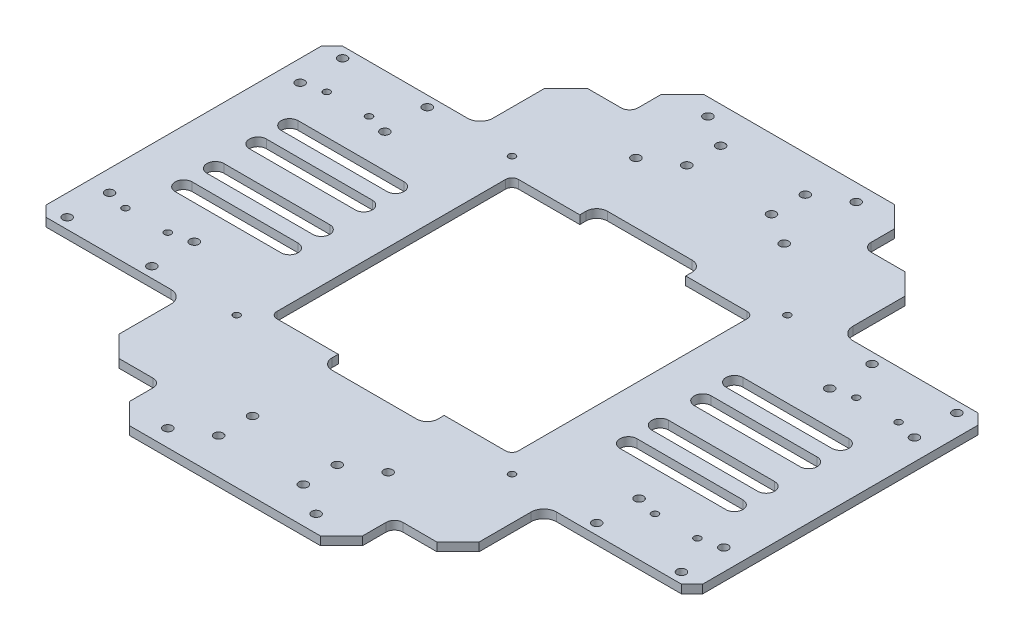
SolidWorks part; units mm, degrees
ref_plane "前视基准面" through (0, 0, 0) normal (0, 0, 1) x (1, 0, 0)
ref_plane "上视基准面" through (0, 0, 0) normal (0, 1, 0) x (1, 0, 0)
ref_plane "右视基准面" through (0, 0, 0) normal (1, 0, 0) x (0, 0, -1)
sketch "草图1" plane through (0, 0, 0) normal (0, 1, 0) x (1, 0, 0)
  line L0 (-55, 135.4999) -> (-55, -135.4999)
  line L1 (-55, -135.4999) -> (55, -135.4999)
  line L2 (55, -135.4999) -> (55, 135.4999)
  line L3 (55, 135.4999) -> (-55, 135.4999)
  circle A0 centre (-35, 127.4999) radius 2.1
  circle A1 centre (-20, 118.4999) radius 2.1
  circle A2 centre (20, 118.4999) radius 2.1
  circle A3 centre (35, 127.4999) radius 2.1
  circle A4 centre (20, 102.4999) radius 2.1
  circle A5 centre (35, 93.4999) radius 2.1
  circle A6 centre (-35, 93.4999) radius 2.1
  circle A7 centre (-20, 102.4999) radius 2.1
  circle A8 centre (-35, -127.4999) radius 2.1
  circle A9 centre (-20, -118.4999) radius 2.1
  circle A10 centre (-20, -102.4999) radius 2.1
  circle A11 centre (20, -118.4999) radius 2.1
  circle A12 centre (20, -102.4999) radius 2.1
  circle A13 centre (35, -93.4999) radius 2.1
  circle A14 centre (35, -127.4999) radius 2.1
extrude "凸台-拉伸1" add sketch "草图1" along normal blind 4
chamfer "倒角1" distance 10 angle 45 4 edges at (-55, 2, 135.4999) (55, 2, 135.4999) (55, 2, -135.4999) (-55, 2, -135.4999)
sketch "草图2" plane through (0, 4, 0) normal (0, 1, 0) x (1, 0, 0)
  line L0 (-25, 45) -> (-40, 30)
  line L1 (-25, -65) -> (25, -65)
  line L2 (-25, -65) -> (-25, -45)
  line L3 (-25, 65) -> (25, 65)
  line L4 (25, -65) -> (25, -45)
  line L5 (-25, -65) -> (25, 65) construction
  line L6 (-25, 65) -> (25, -65) construction
  line L7 (-40, 30) -> (-40, -30)
  line L8 (25, 45) -> (25, 65)
  line L9 (-25, 45) -> (-25, 65)
  line L10 (0, 65) -> (0, -65) construction
  line L11 (25, 0) -> (-25, 0) construction
  line L13 (25, 45) -> (40, 30)
  line L14 (40, 30) -> (40, -30)
  line L15 (25, -45) -> (40, -30)
  line L16 (-25, -45) -> (-40, -30)
  point P0 (0, 0)
  dimension "D1" = 130
  dimension "D2" = 50
  dimension "D5" = 20
extrude "切除-拉伸1" cut sketch "草图2" against normal blind 4
fillet "圆角1" radius 5 4 edges at (-25, 2, 65) (25, 2, 65) (25, 2, -65) (-25, 2, -65)
sketch "草图3" plane through (0, 4, 0) normal (0, 1, 0) x (1, 0, 0)
  line L0 (55, 110.4999) -> (85, 110.4999)
  line L1 (-55, 125.4999) -> (-55, -125.4999) construction
  line L2 (-85, 93.4999) -> (-85, -102.4999)
  line L3 (55, -102.4999) -> (55, 93.4999)
  line L4 (-55, -102.4999) -> (-55, 93.4999)
  line L5 (0, 135.4999) -> (0, -135.4999) construction
  line L6 (45, 135.4999) -> (-45, 135.4999) construction
  line L7 (-45, -135.4999) -> (45, -135.4999) construction
  line L10 (85, 93.4999) -> (85, -102.4999)
  line L12 (55, -125.4999) -> (55, 125.4999) construction
  line L13 (-55, 110.4999) -> (-85, 110.4999)
  line L14 (-85, 110.4999) -> (-85, 93.4999)
  line L15 (-55, 93.4999) -> (-55, 110.4999)
  line L16 (85, 110.4999) -> (85, 93.4999)
  line L17 (55, 110.4999) -> (55, 93.4999)
  line L20 (-55, -110.4999) -> (-85, -110.4999)
  line L21 (-85, -110.4999) -> (-85, -102.4999)
  line L22 (-55, -102.4999) -> (-55, -110.4999)
  line L23 (85, -102.4999) -> (85, -110.4999)
  line L24 (85, -110.4999) -> (55, -110.4999)
  line L25 (55, -110.4999) -> (55, -102.4999)
extrude "凸台-拉伸2" add sketch "草图3" against normal blind 4
chamfer "倒角2" distance 10 angle 45 4 edges at (-85, 2, -110.4999) (-85, 2, 110.4999) (85, 2, 110.4999) (85, 2, -110.4999)
fillet "圆角2" radius 4 4 edges
fillet "圆角3" radius 5 4 edges at (-40, 2, 30) (40, 2, 30) (40, 2, -30) (-40, 2, -30)
sketch "草图5" plane through (0, 4, 0) normal (0, 1, 0) x (1, 0, 0)
  line L1 (-65, -65) -> (65, -65) construction
  line L2 (-65, -65) -> (-65, 65) construction
  line L3 (-65, 65) -> (65, 65) construction
  line L4 (65, -65) -> (65, 65) construction
  line L5 (-65, -65) -> (65, 65) construction
  line L6 (-65, 65) -> (65, -65) construction
  circle A0 centre (-65, 65) radius 1.6
  circle A1 centre (65, 65) radius 1.6
  circle A2 centre (65, -65) radius 1.6
  circle A3 centre (-65, -65) radius 1.6
  point P0 (0, 0)
  dimension "D1" = 130
  dimension "D2" = 130
extrude "切除-拉伸2" cut sketch "草图5" against normal blind 4
sketch "草图7" plane through (0, 4, 0) normal (0, 1, 0) x (1, 0, 0)
  line L0 (-85, 0) -> (-85, 70)
  line L1 (-85, 100.4999) -> (-85, -100.4999) construction
  line L2 (-85, 70) -> (-155, 70)
  line L3 (-155, 70) -> (-155, -70)
  line L4 (-155, -70) -> (-85, -70)
  line L5 (-85, -70) -> (-85, 0)
  line L6 (85, 70) -> (155, 70)
  line L7 (85, -100.4999) -> (85, 100.4999) construction
  line L8 (155, 70) -> (155, -70)
  line L9 (155, -70) -> (85, -70)
  line L10 (85, -70) -> (85, 70)
extrude "凸台-拉伸3" add sketch "草图7" against normal blind 4
fillet "圆角4" radius 6 12 edges
sketch "草图8" plane through (0, 4, 0) normal (0, 1, 0) x (1, 0, 0)
  line L0 (0, 135.4999) -> (0, 0) construction
  circle A0 centre (105, 65) radius 2.1
  circle A1 centre (145, 65) radius 2.1
  circle A2 centre (145, 45) radius 2.1
  circle A3 centre (105, 45) radius 2.1
  circle A4 centre (145, -45) radius 2.1
  circle A5 centre (145, -65) radius 2.1
  circle A6 centre (105, -65) radius 2.1
  circle A7 centre (105, -45) radius 2.1
  circle A8 centre (-145, 65) radius 2.1
  circle A9 centre (-105, 65) radius 2.1
  circle A10 centre (-105, 45) radius 2.1
  circle A11 centre (-145, 45) radius 2.1
  circle A12 centre (-145, -45) radius 2.1
  circle A13 centre (-105, -45) radius 2.1
  circle A14 centre (-105, -65) radius 2.1
  circle A15 centre (-145, -65) radius 2.1
extrude "切除-拉伸3" cut sketch "草图8" against normal blind 4
sketch "草图9" plane through (0, 4, 0) normal (0, 1, 0) x (1, 0, 0)
  line L0 (-105, 42.9) -> (-105, 25.0287) construction
  line L1 (-130, 25.0287) -> (-80, 25.0287) construction
  line L2 (-130, 29.0287) -> (-80, 29.0287)
  line L3 (-130, 21.0287) -> (-80, 21.0287)
  line L4 (-130, 10.0287) -> (-80, 10.0287) construction
  line L5 (-130, 14.0287) -> (-80, 14.0287)
  line L6 (-130, 6.0287) -> (-80, 6.0287)
  line L7 (-155, 0) -> (0, 0) construction
  line L8 (-155, 70) -> (-155, -70) construction
  line L9 (0, 0) -> (0, 135.4999) construction
  line L10 (45, 135.4999) -> (-45, 135.4999) construction
  line L11 (-130, -25.0287) -> (-80, -25.0287) construction
  line L12 (-130, -29.0287) -> (-80, -29.0287)
  line L13 (-130, -21.0287) -> (-80, -21.0287)
  line L14 (-130, -10.0287) -> (-80, -10.0287) construction
  line L15 (-130, -14.0287) -> (-80, -14.0287)
  line L16 (-130, -6.0287) -> (-80, -6.0287)
  line L17 (130, 25.0287) -> (80, 25.0287) construction
  line L18 (130, 29.0287) -> (80, 29.0287)
  line L19 (130, 21.0287) -> (80, 21.0287)
  line L20 (130, 10.0287) -> (80, 10.0287) construction
  line L21 (130, 14.0287) -> (80, 14.0287)
  line L22 (130, 6.0287) -> (80, 6.0287)
  line L23 (130, -25.0287) -> (80, -25.0287) construction
  line L24 (130, -29.0287) -> (80, -29.0287)
  line L25 (130, -21.0287) -> (80, -21.0287)
  line L26 (130, -10.0287) -> (80, -10.0287) construction
  line L27 (130, -14.0287) -> (80, -14.0287)
  line L28 (130, -6.0287) -> (80, -6.0287)
  line L29 (-145, 45) -> (-145, 47.5) construction
  line L30 (-145, 47.5) -> (-105, 47.5) construction
  line L31 (-105, 47.5) -> (-105, 45) construction
  line L32 (-125, 47.5) -> (-125, 56.2221) construction
  line L33 (-125, -47.5) -> (-125, -56.2221) construction
  line L34 (-105, -47.5) -> (-105, -45) construction
  line L35 (-145, -47.5) -> (-105, -47.5) construction
  line L36 (-145, -45) -> (-145, -47.5) construction
  line L37 (145, -45) -> (145, -47.5) construction
  line L38 (145, -47.5) -> (105, -47.5) construction
  line L39 (105, -47.5) -> (105, -45) construction
  line L40 (125, -47.5) -> (125, -56.2221) construction
  line L41 (125, 47.5) -> (125, 56.2221) construction
  line L42 (105, 47.5) -> (105, 45) construction
  line L43 (145, 47.5) -> (105, 47.5) construction
  line L44 (145, 45) -> (145, 47.5) construction
  circle A0 centre (-105, 45) radius 2.1 construction
  arc A1 (-130, 29.0287) -> (-130, 21.0287) centre (-130, 25.0287) ccw
  arc A2 (-80, 21.0287) -> (-80, 29.0287) centre (-80, 25.0287) ccw
  arc A3 (-130, 14.0287) -> (-130, 6.0287) centre (-130, 10.0287) ccw
  arc A4 (-80, 6.0287) -> (-80, 14.0287) centre (-80, 10.0287) ccw
  arc A5 (-130, -29.0287) -> (-130, -21.0287) centre (-130, -25.0287) cw
  arc A6 (-80, -21.0287) -> (-80, -29.0287) centre (-80, -25.0287) cw
  arc A7 (-130, -14.0287) -> (-130, -6.0287) centre (-130, -10.0287) cw
  arc A8 (-80, -6.0287) -> (-80, -14.0287) centre (-80, -10.0287) cw
  arc A9 (130, 29.0287) -> (130, 21.0287) centre (130, 25.0287) cw
  arc A10 (80, 21.0287) -> (80, 29.0287) centre (80, 25.0287) cw
  arc A11 (130, 14.0287) -> (130, 6.0287) centre (130, 10.0287) cw
  arc A12 (80, 6.0287) -> (80, 14.0287) centre (80, 10.0287) cw
  arc A13 (130, -29.0287) -> (130, -21.0287) centre (130, -25.0287) ccw
  arc A14 (80, -21.0287) -> (80, -29.0287) centre (80, -25.0287) ccw
  arc A15 (130, -14.0287) -> (130, -6.0287) centre (130, -10.0287) ccw
  arc A16 (80, -6.0287) -> (80, -14.0287) centre (80, -10.0287) ccw
  circle A17 centre (-135, 47.5) radius 1.6
  circle A18 centre (-115, 47.5) radius 1.6
  circle A19 centre (-115, -47.5) radius 1.6
  circle A20 centre (-135, -47.5) radius 1.6
  circle A21 centre (135, -47.5) radius 1.6
  circle A22 centre (115, -47.5) radius 1.6
  circle A23 centre (115, 47.5) radius 1.6
  circle A24 centre (135, 47.5) radius 1.6
  point P7 (-105, 25.0287)
  point P15 (-105, 10.0287)
  point P29 (-105, -25.0287)
  point P36 (-105, -10.0287)
  point P43 (105, 25.0287)
  point P50 (105, 10.0287)
  point P57 (105, -25.0287)
  point P64 (105, -10.0287)
  dimension "D1" = 4
  dimension "D4" = 10
  dimension "D2" = 50
  dimension "D3" = 2
extrude "切除-拉伸4" cut sketch "草图9" against normal blind 4
chamfer "倒角3" distance 5 angle 45 4 edges at (155, 2, -70) (155, 2, 70) (-155, 2, 70) (-155, 2, -70)
sketch "草图11" plane through (0, 4, 0) normal (0, 1, 0) x (1, 0, 0)
  line L0 (-55, 55.0142) -> (55, 55.0142) construction
  line L1 (-55, 55.0142) -> (-55, -55.0142) construction
  line L2 (-55, -55.0142) -> (55, -55.0142) construction
  line L3 (55, 55.0142) -> (55, -55.0142) construction
  line L4 (-55, 55.0142) -> (55, -55.0142) construction
  line L5 (-55, -55.0142) -> (55, 55.0142) construction
  line L6 (-57, 57.0142) -> (57, 57.0142)
  line L7 (57, 57.0142) -> (57, -57.0142)
  line L8 (-57, -57.0142) -> (57, -57.0142)
  line L9 (-57, 57.0142) -> (-57, -57.0142)
  point P0 (0, 0)
  dimension "D1" = 2
extrude "切除-拉伸5" cut sketch "草图11" against normal blind 10
fillet "圆角5" radius 3 4 edges at (-57, 2, 57.0142) (57, 2, 57.0142) (57, 2, -57.0142) (-57, 2, -57.0142)
